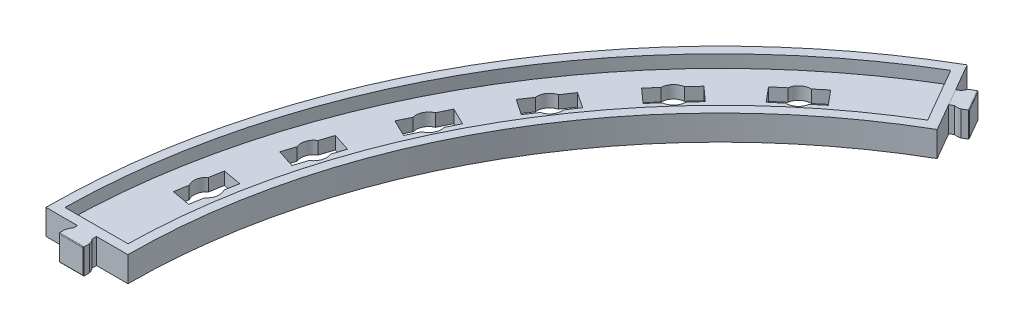
SolidWorks part; units mm, degrees
ref_plane "前视基准面" through (0, 0, 0) normal (0, 0, 1) x (1, 0, 0)
ref_plane "上视基准面" through (0, 0, 0) normal (0, 1, 0) x (1, 0, 0)
ref_plane "右视基准面" through (0, 0, 0) normal (1, 0, 0) x (0, 0, -1)
sketch "草图1" plane through (0, 0, 0) normal (0, 1, 0) x (1, 0, 0)
  line L0 (0, 0) -> (-94, 0) construction
  line L1 (0, 0) -> (-47, 81.4064) construction
  line L2 (-94, 0) -> (-107, 0)
  line L3 (-47, 81.4064) -> (-53.5, 92.6647)
  arc A0 (-47, 81.4064) -> (-94, 0) centre (0, 0) ccw
  arc A1 (-53.5, 92.6647) -> (-107, 0) centre (0, 0) ccw
  dimension "D2" = 13
  dimension "D3" = 214
  dimension "D1" = 60
extrude "凸台-拉伸1" add sketch "草图1" along normal blind 2
sketch "草图2" plane through (0, 2, 0) normal (0, 1, 0) x (1, 0, 0)
  line L0 (-105.4893, 1.5) -> (-95.4882, 1.5)
  line L1 (-49.0431, 81.9452) -> (-54.0437, 90.6064)
  line L2 (-47, 81.4064) -> (-53.5, 92.6647)
  line L3 (-107, 0) -> (-94, 0)
  line L4 (-47, 81.4064) -> (-53.5, 92.6647)
  line L5 (-107, 0) -> (-94, 0)
  arc A0 (-54.0437, 90.6064) -> (-105.4893, 1.5) centre (0, 0) ccw
  arc A1 (-49.0431, 81.9452) -> (-95.4882, 1.5) centre (0, 0) ccw
  arc A2 (-47, 81.4064) -> (-94, 0) centre (0, 0) ccw
  arc A3 (-53.5, 92.6647) -> (-107, 0) centre (0, 0) ccw
  arc A4 (-47, 81.4064) -> (-94, 0) centre (0, 0) ccw
  arc A5 (-53.5, 92.6647) -> (-107, 0) centre (0, 0) ccw
  dimension "D1" = 0
  dimension "D2" = 1.5
extrude "凸台-拉伸2" add sketch "草图2" along normal blind 2
sketch "草图3" plane through (0, 4, 0) normal (0, 1, 0) x (1, 0, 0)
  line L0 (-50.25, 87.0356) -> (-48.5179, 88.0356) construction
  line L1 (-47, 81.4064) -> (-53.5, 92.6647) construction
  line L2 (-48.5179, 88.0356) -> (-48.0849, 88.2856) construction
  line L3 (-49.5, 85.7365) -> (-51, 88.3346)
  line L4 (-51, 88.3346) -> (-50.4136, 88.6732)
  line L5 (-47.1099, 86.5968) -> (-49.0599, 89.9743)
  line L6 (-49.0599, 89.9743) -> (-49.8778, 89.5021)
  line L7 (-47.1099, 86.5968) -> (-47.9278, 86.1246)
  line L8 (-49.5, 85.7365) -> (-48.9136, 86.0751)
  arc A0 (-49.8778, 89.5021) -> (-50.4136, 88.6732) centre (-48.5179, 88.0356) ccw
  arc A1 (-47.9278, 86.1246) -> (-48.9136, 86.0751) centre (-48.5179, 88.0356) cw
  dimension "D7" = 2
  dimension "D2" = 2
  dimension "D3" = 0.5
  dimension "D4" = 1.5
  dimension "D6" = 1.95
extrude "凸台-拉伸3" add sketch "草图3" against normal blind 4 separate body
sketch "草图4" plane through (0, 4, 0) normal (0, 1, 0) x (1, 0, 0)
  line L0 (-100.5, 0) -> (-100.5, -2) construction
  line L1 (-107, 0) -> (-94, 0) construction
  line L2 (-100.5, -2) -> (-100.5, -2.5) construction
  line L3 (-99, 0) -> (-102, 0)
  line L4 (-102, 0) -> (-102, -0.6771)
  line L5 (-98.55, -2.5) -> (-102.45, -2.5)
  line L6 (-102.45, -2.5) -> (-102.45, -1.5556)
  line L7 (-98.55, -2.5) -> (-98.55, -1.5556)
  line L8 (-99, 0) -> (-99, -0.6771)
  arc A0 (-102, -0.6771) -> (-102.45, -1.5556) centre (-100.5, -2) ccw
  arc A1 (-99, -0.6771) -> (-98.55, -1.5556) centre (-100.5, -2) cw
  dimension "D5" = 2
  dimension "D1" = 2
  dimension "D2" = 0.5
  dimension "D3" = 1.5
  dimension "D4" = 1.95
extrude "凸台-拉伸4" add sketch "草图4" against normal blind 4
sketch "草图5" plane through (0, 2, 0) normal (0, 1, 0) x (1, 0, 0)
  line L0 (0, 0) -> (-87.0356, 50.25) construction
  line L1 (-87.4463, 46.5445) -> (-88.4007, 44.5877)
  line L2 (-99, 0) -> (-94, 0) construction
  line L3 (0, 0) -> (-90.3288, 44.0563) construction
  line L4 (-87.4463, 46.5445) -> (-90.1427, 47.8596)
  line L5 (-90.5149, 40.253) -> (-93.2113, 41.5681)
  line L6 (-90.1427, 47.8596) -> (-91.0971, 45.9028)
  line L7 (-87.4463, 46.5445) -> (-93.2113, 41.5681) construction
  line L8 (-90.5149, 40.253) -> (-90.1427, 47.8596) construction
  line L9 (-89.5605, 42.2098) -> (-90.5149, 40.253)
  line L10 (-92.2569, 43.5249) -> (-93.2113, 41.5681)
  arc A0 (-91.0971, 45.9028) -> (-92.2569, 43.5249) centre (-90.3288, 44.0563) ccw
  circle A1 centre (0, 0) radius 100.5 construction
  arc A2 (-89.5605, 42.2098) -> (-88.4007, 44.5877) centre (-90.3288, 44.0563) ccw
  dimension "D1" = 30
  dimension "D2" = 201
  dimension "D4" = 4
  dimension "D3" = 4
  dimension "D5" = 90
  dimension "D6" = 3
  dimension "D7" = 7
extrude "切除-拉伸1" cut sketch "草图5" against normal up to next (2 mm away)
pattern_circular "阵列(圆周)1" count 3 over 16 about axis through (0, 0, 0) along (0, 1, 0) of "切除-拉伸1"
pattern_circular "阵列(圆周)2" count 4 over 24 about axis through (0, 0, 0) along (0, 1, 0) of "切除-拉伸1"
fillet "圆角1" radius 0.1 4 edges at (-98.55, 2, 2.5) (-100.5, 4, 2.5) (-100.5, 0, 2.5) (-102.45, 2, 2.5)
fillet "圆角2" radius 0.1 4 edges at (-49.0599, 2, -89.9743) (-48.0849, 0, -88.2856) (-47.1099, 2, -86.5968) (-48.0849, 4, -88.2856)
